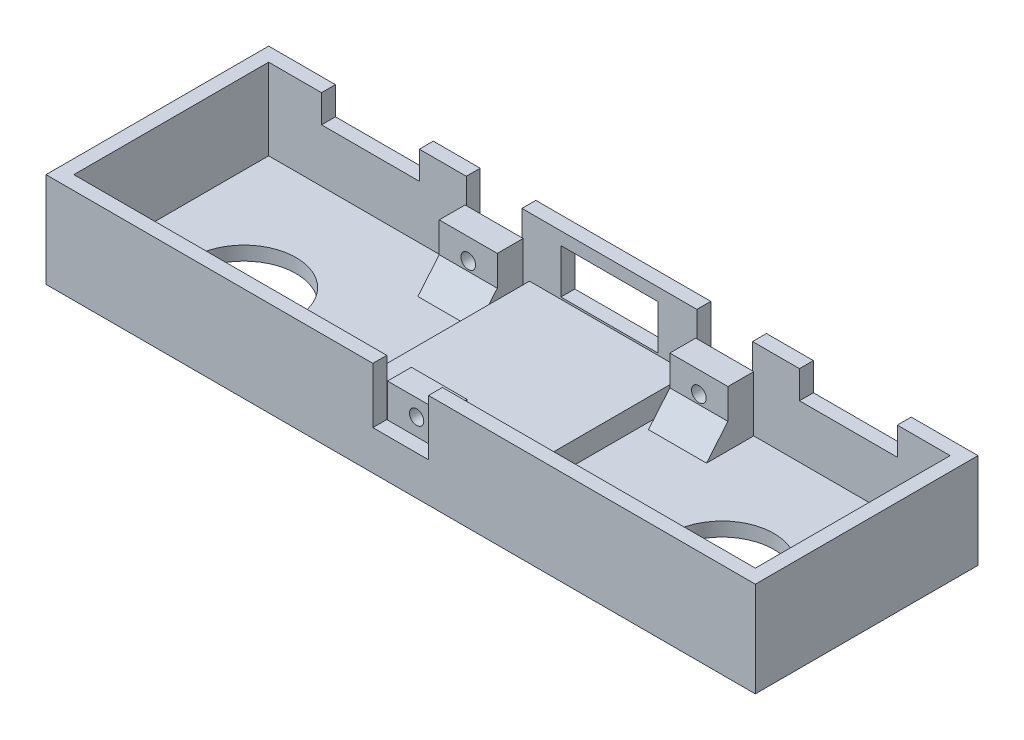
SolidWorks part; units mm, degrees
other "Markup1"
sketch "Sketch25" plane through (89.2, 11.95, -28) normal (0.2712, 0.5466, -0.7923) x (-0.4526, -0.654, -0.6061)
material "Custom Plastic"
ref_plane "Front Plane" through (0, 0, 0) normal (0, 0, 1) x (1, 0, 0)
ref_plane "Top Plane" through (0, 0, 0) normal (0, 1, 0) x (1, 0, 0)
ref_plane "Right Plane" through (0, 0, 0) normal (1, 0, 0) x (0, 0, -1)
sketch "Sketch1" plane through (0, 0, 0) normal (0, 1, 0) x (1, 0, 0)
  line L1 (0, 0) -> (89.2, 0)
  line L2 (0, 0) -> (0, 28)
  line L3 (0, 28) -> (89.2, 28)
  line L4 (89.2, 0) -> (89.2, 28)
  dimension "D1" = 89.2
  dimension "D2" = 28
extrude "Boss-Extrude1" add sketch "Sketch1" along normal blind 11.95
shell "Shell1" thickness 1.75
sketch "Sketch2" plane through (0, 1.75, 0) normal (0, 1, 0) x (1, 0, 0)
  line L0 (0, 0) -> (89.2, 0) construction
  line L1 (0, 28) -> (0, 0) construction
  circle A0 centre (14.55, 10.35) radius 6.55
  circle A1 centre (74.65, 10.35) radius 6.55
  dimension "D1" = 13.1
  dimension "D2" = 13.1
  dimension "D3" = 10.35
  dimension "D4" = 10.35
  dimension "D5" = 60.1
  dimension "D6" = 14.55
extrude "Cut-Extrude1" cut sketch "Sketch2" against normal through all
sketch "Sketch3" plane through (0, 0, -26.25) normal (0, 0, 1) x (1, 0, 0)
  line L0 (0, 11.95) -> (89.2, 11.95) construction
  line L1 (8.4, 11.95) -> (20.7, 11.95)
  line L2 (8.4, 11.95) -> (8.4, 8.45)
  line L3 (8.4, 8.45) -> (20.7, 8.45)
  line L4 (20.7, 11.95) -> (20.7, 8.45)
  line L5 (44.6, -9.9306) -> (44.6, 19.574) construction
  line L6 (0, 11.95) -> (0, 0) construction
  line L7 (80.8, 11.95) -> (68.5, 11.95)
  line L8 (80.8, 11.95) -> (80.8, 8.45)
  line L9 (80.8, 8.45) -> (68.5, 8.45)
  line L10 (68.5, 11.95) -> (68.5, 8.45)
  dimension "D1" = 44.6
  dimension "D2" = 3.5
  dimension "D3" = 12.3
  dimension "D4" = 8.4
extrude "Cut-Extrude2" cut sketch "Sketch3" against normal blind 11.95
sketch "Sketch4" plane through (0, 0, -26.25) normal (0, 0, 1) x (1, 0, 0)
  line L0 (44.6, -6.2785) -> (44.6, 15.7298) construction
  line L2 (38.5, 4.75) -> (50.7, 4.75)
  line L3 (38.5, 4.75) -> (38.5, 10.35)
  line L4 (38.5, 10.35) -> (50.7, 10.35)
  line L5 (50.7, 4.75) -> (50.7, 10.35)
  line L6 (0, 11.95) -> (89.2, 11.95) construction
  point P7 (44.6, 10.35)
  dimension "D1" = 44.6
  dimension "D2" = 1.6
  dimension "D3" = 12.2
  dimension "D4" = 5.6
extrude "Cut-Extrude3" cut sketch "Sketch4" against normal blind 11.95
sketch "Sketch5" plane through (0, 1.75, 0) normal (0, 1, 0) x (1, 0, 0)
  line L0 (44.6, 37.0174) -> (44.6, -9.498) construction
  line L1 (0, 28) -> (0, 0) construction
  line L2 (1.75, 1.75) -> (87.45, 1.75) construction
  line L3 (34.55, 1.75) -> (54.65, 1.75)
  line L4 (34.55, 1.75) -> (34.55, 26.25)
  line L5 (34.55, 26.25) -> (54.65, 26.25)
  line L6 (54.65, 1.75) -> (54.65, 26.25)
  line L7 (68.5, 26.25) -> (20.7, 26.25) construction
  point P12 (44.6, 1.75)
  dimension "D1" = 44.6
  dimension "D2" = 20.1
extrude "Boss-Extrude2" add sketch "Sketch5" along normal blind 2.75
sketch "Sketch6" plane through (0, 0, 0) normal (0, -1, 0) x (1, 0, 0)
  line L0 (36.55, -1.75) -> (36.55, -26)
  line L1 (52.65, -1.75) -> (52.65, -26)
  line L3 (34.55, -26.25) -> (34.55, -1.75) construction
  line L4 (54.65, -1.75) -> (54.65, -26.25) construction
  line L5 (36.55, -26) -> (52.65, -26)
  line L6 (89.2, -28) -> (0, -28) construction
  line L8 (34.55, -1.75) -> (34.55, -26.25)
  line L9 (54.65, -1.75) -> (34.55, -1.75)
  line L10 (54.65, -26.25) -> (54.65, -1.75)
  line L11 (34.55, -26.25) -> (54.65, -26.25)
  line L17 (52.65, -1.75) -> (36.55, -1.75)
  dimension "D2" = 2
  dimension "D3" = 2
  dimension "D4" = 2
  dimension "D1" = 0
extrude "Cut-Extrude4" cut sketch "Sketch6" against normal blind 3.95
sketch "Sketch8" plane through (0, 0, -28) normal (0, 0, -1) x (-1, 0, 0)
  line L0 (-50.7, 3.45) -> (-38.5, 3.45)
  line L1 (-38.5, 4.75) -> (-50.7, 4.75) construction
  line L2 (-52.65, 0) -> (-50.7, 3.45)
  line L3 (-36.55, 0) -> (-38.5, 3.45)
  line L4 (-52.65, 0) -> (-36.55, 0)
  line L5 (-52.65, 3.95) -> (-52.65, 0)
  line L6 (-36.55, 3.95) -> (-52.65, 3.95)
  line L7 (-36.55, 0) -> (-36.55, 3.95)
  line L8 (-52.65, 0) -> (-36.55, 0)
  dimension "D2" = 1.3
  dimension "D1" = 0
extrude "Cut-Extrude6" cut sketch "Sketch8" against normal up to surface (2 mm away) up to face at (44.6, 1.975, -26)
ref_plane "Plane1" through (44.6, 0, 0) normal (-1, 0, 0) x (0, 0, 1)
ref_plane "Plane2" through (44.6, 0, 0) normal (1, 0, 0) x (0, 0, -1)
sketch "Sketch14" plane through (0, 0, 0) normal (0, 0, 1) x (1, 0, 0)
  line L2 (48.1, 11.95) -> (41.1, 11.95)
  line L3 (0, 11.95) -> (89.2, 11.95) construction
  line L5 (41.1, 11.95) -> (41.1, 4.95)
  line L6 (41.1, 4.95) -> (48.1, 4.95)
  line L7 (48.1, 4.95) -> (48.1, 11.95)
  line L8 (44.6, 17.45) -> (44.6, -8.35) construction
  point P8 (44.6, 11.95)
  dimension "D1" = 7
  dimension "D2" = 7
extrude "Cut-Extrude10" cut sketch "Sketch14" against normal up to next
sketch "Sketch15" plane through (0, 4.75, 0) normal (0, 1, 0) x (1, 0, 0)
  line L6 (41.1, 1.85) -> (41.1, 4.85)
  line L7 (41.1, 4.85) -> (48.1, 4.85)
  line L8 (48.1, 4.85) -> (48.1, 1.85)
  line L9 (41.1, 1.85) -> (48.1, 1.85)
  line L32 (41.1, 1.75) -> (48.1, 1.75) construction
  line L33 (41.1, 1.75) -> (41.1, 0) construction
  line L34 (48.1, 1.75) -> (48.1, 0) construction
  point P9 (39.6, 2)
  point P11 (49.6, 2)
  dimension "D2" = 3
  dimension "D1" = 0.1
extrude "Boss-Extrude3" add sketch "Sketch15" along normal up to surface (4.35 mm away) contours L6 L7 L8 L9
sketch "Sketch16" plane through (48.1, 0, 0) normal (1, 0, 0) x (0, 0, -1)
  line L0 (4.85, 7.5675) -> (8.0209, 4.75)
  line L1 (8.0209, 4.75) -> (4.85, 4.75)
  line L4 (4.85, 9.1) -> (1.85, 9.1)
  line L5 (1.85, 9.1) -> (1.85, 4.75)
  line L7 (4.85, 4.75) -> (4.85, 9.1)
  line L11 (4.85, 4.75) -> (4.85, 7.5675)
  line L14 (1.85, 4.75) -> (4.85, 4.75)
  dimension "D1" = 0
extrude "Boss-Extrude5" add sketch "Sketch16" against normal up to surface (7 mm away) up to face at (41.1, 6.925, -3.35)
sketch "Sketch17" plane through (0, 0, -28) normal (0, 0, -1) x (-1, 0, 0)
  line L0 (0, 11.95) -> (-26.75, 11.95) construction
  line L1 (-62.6, 3.45) -> (-55.6, 3.45)
  line L2 (-62.6, 3.45) -> (-62.6, 11.95)
  line L3 (-62.6, 11.95) -> (-55.6, 11.95)
  line L4 (-55.6, 3.45) -> (-55.6, 11.95)
  line L5 (-44.6, 17.45) -> (-44.6, -16.5653) construction
  line L6 (-33.6, 3.45) -> (-26.6, 3.45)
  line L7 (-33.6, 3.45) -> (-33.6, 11.95)
  line L8 (-33.6, 11.95) -> (-26.6, 11.95)
  line L9 (-26.6, 3.45) -> (-26.6, 11.95)
  dimension "D1" = 8.5
  dimension "D2" = 7
  dimension "D3" = 8.5
  dimension "D4" = 7
  dimension "D5" = 11
  dimension "D6" = 11
extrude "Cut-Extrude11" cut sketch "Sketch17" against normal up to next (1.75 mm away)
ref_plane "Plane3" through (44.6, 0, 0) normal (1, 0, 0) x (0, 0, -1)
ref_plane "Plane4" through (44.6, 0, 0) normal (1, 0, 0) x (0, 0, -1)
sketch "Sketch18" plane through (0, 1.75, 0) normal (0, 1, 0) x (1, 0, 0)
  line L13 (44.6, 26.25) -> (44.6, 49.4523) construction
  line L22 (55.6, 26.25) -> (33.6, 26.25) construction
  line L23 (62.75, 26.25) -> (55.45, 26.25)
  line L24 (55.45, 26.25) -> (55.45, 23)
  line L25 (62.75, 26.25) -> (62.75, 23)
  line L26 (62.75, 23) -> (55.45, 23)
  line L29 (87.45, 26.25) -> (54.65, 26.25) construction
  line L32 (26.45, 26.25) -> (26.45, 23)
  line L33 (26.45, 23) -> (33.75, 23)
  line L34 (33.75, 26.25) -> (33.75, 23)
  line L35 (26.45, 26.25) -> (33.75, 26.25)
  dimension "D3" = 10.85
  dimension "D2" = 7.3
  dimension "D1" = 3.25
extrude "Boss-Extrude6" add sketch "Sketch18" along normal blind 7
ref_plane "Plane5" through (44.6, 0, 0) normal (1, 0, 0) x (0, 0, -1)
sketch "Sketch20" plane through (0, 0, -26.25) normal (0, 0, -1) x (-1, 0, 0)
  line L0 (-62.6, 11.95) -> (-62.6, 3.45) construction
  line L1 (-62.6, 3.45) -> (-55.6, 3.45) construction
  line L2 (-33.6, 3.45) -> (-26.6, 3.45) construction
  line L3 (-33.6, 11.95) -> (-33.6, 3.45) construction
  circle A4 centre (-59.1, 6.1) radius 0.925
  circle A5 centre (-30.1, 6.1) radius 0.925
  dimension "D1" = 3.5
  dimension "D2" = 1.85
  dimension "D3" = 1.85
  dimension "D4" = 2.65
  dimension "D5" = 2.65
  dimension "D6" = 3.5
extrude "Cut-Extrude12" cut sketch "Sketch20" against normal up to next (3.25 mm away)
sketch "Sketch26" plane through (0, 0, -1.85) normal (0, 0, 1) x (1, 0, 0)
  line L0 (41.1, 9.1) -> (41.1, 4.75) construction
  line L1 (48.1, 9.1) -> (41.1, 9.1) construction
  circle A0 centre (44.7553, 7) radius 0.9
  dimension "D1" = 1.8
  dimension "D2" = 3.6553
  dimension "D3" = 2.1
extrude "Cut-Extrude14" cut sketch "Sketch26" against normal up to surface (3.6387 mm away)
sketch "Sketch27" plane through (26.45, 0, 0) normal (-1, 0, 0) x (0, 0, 1)
  line L0 (-23, 1.75) -> (-20.31, 1.75)
  line L1 (-20.31, 1.75) -> (-23, 4.9558)
  line L4 (-26.25, 1.75) -> (-23, 1.75)
  line L5 (-23, 1.75) -> (-23, 8.75)
  line L6 (-23, 8.75) -> (-26.25, 8.75)
  line L7 (-26.25, 8.75) -> (-26.25, 1.75)
  line L9 (-23, 1.75) -> (-23, 4.9558)
  dimension "D2" = 50
  dimension "D3" = 2.69
  dimension "D1" = 0
extrude "Boss-Extrude9" add sketch "Sketch27" against normal up to surface (7.3 mm away) up to face at (33.75, 5.25, -24.625)
sketch "Sketch28" plane through (62.75, 0, 0) normal (1, 0, 0) x (0, 0, -1)
  line L0 (23, 1.75) -> (20.31, 1.75)
  line L1 (20.31, 1.75) -> (23, 4.9558)
  line L4 (23, 1.75) -> (26.25, 1.75)
  line L5 (26.25, 1.75) -> (26.25, 8.75)
  line L6 (26.25, 8.75) -> (23, 8.75)
  line L7 (23, 8.75) -> (23, 1.75)
  line L11 (23, 4.9558) -> (23, 1.75)
  dimension "D2" = 50
  dimension "D3" = 2.69
  dimension "D1" = 0
extrude "Boss-Extrude10" add sketch "Sketch28" against normal up to surface (7.3 mm away) up to face at (55.45, 5.25, -24.625)
